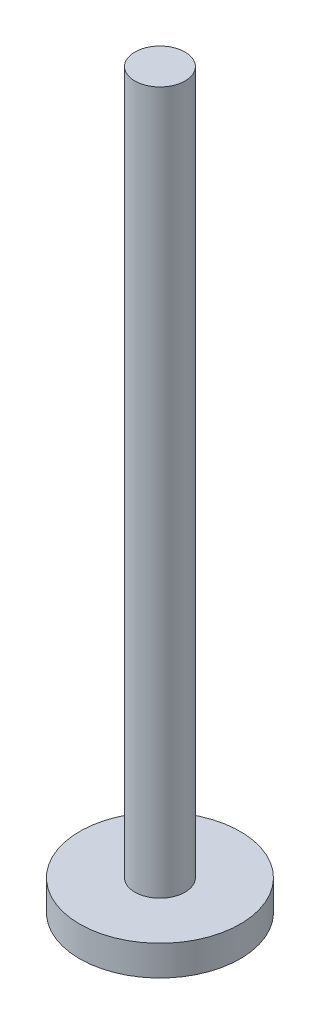
SolidWorks part; units mm, degrees
material "6061-T6 (SS)"
ref_plane "前视基准面" through (0, 0, 0) normal (0, 0, 1) x (1, 0, 0)
ref_plane "上视基准面" through (0, 0, 0) normal (0, 1, 0) x (1, 0, 0)
ref_plane "右视基准面" through (0, 0, 0) normal (1, 0, 0) x (0, 0, -1)
sketch "草图1" plane through (0, 0, 0) normal (0, 1, 0) x (1, 0, 0)
  circle A0 centre (0, 0) radius 8
  dimension "D1" = 16
extrude "凸台-拉伸1" add sketch "草图1" along normal blind 3
sketch "草图2" plane through (0, 3, 0) normal (0, 1, 0) x (1, 0, 0)
  circle A0 centre (0, 0) radius 2.5
  dimension "D1" = 5
extrude "凸台-拉伸2" add sketch "草图2" along normal blind 70
equation "\"行程L\"= 50"
equation "\"D1@凸台-拉伸2\"=\"行程L\"+50"
